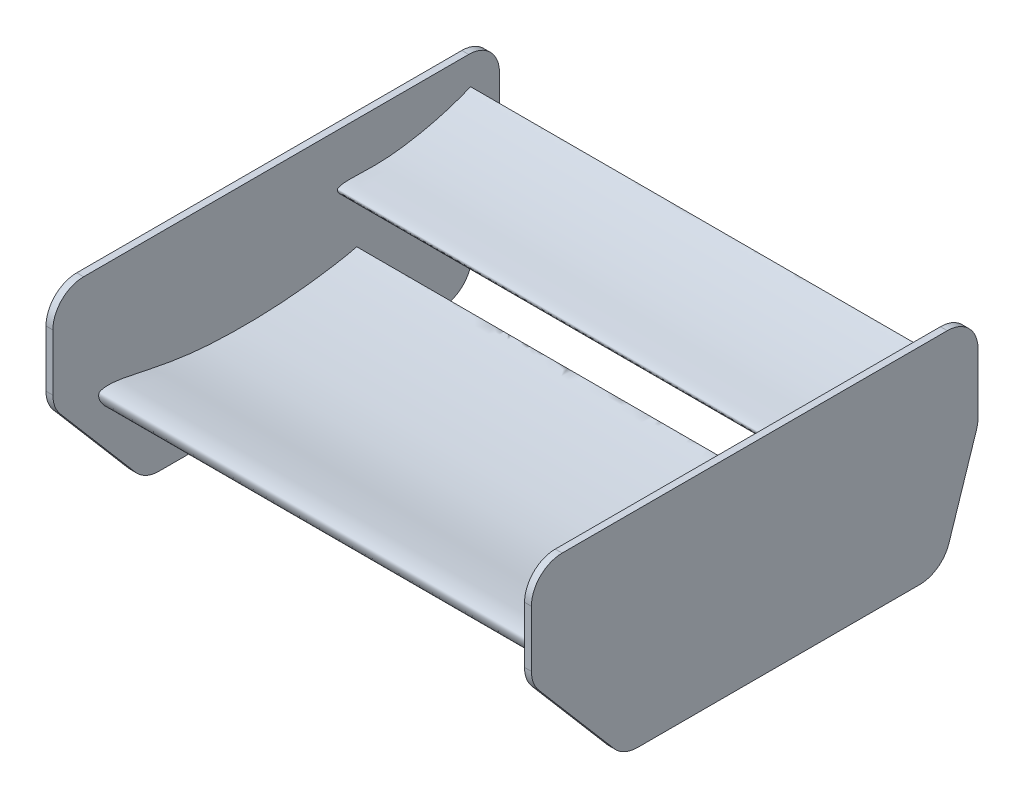
SolidWorks part; units mm, degrees
ref_plane "Front Plane" through (0, 0, 0) normal (0, 0, 1) x (1, 0, 0)
ref_plane "Top Plane" through (0, 0, 0) normal (0, 1, 0) x (1, 0, 0)
ref_plane "Right Plane" through (0, 0, 0) normal (1, 0, 0) x (0, 0, -1)
ref_plane "Soft Top Limit" through (0, 1174.6, 0) normal (0, 1, 0) x (1, 0, 0)
ref_plane "Soft Rear Limit" through (0, 0, -1192.975) normal (0, 0, 1) x (1, 0, 0)
ref_plane "Soft Right Limit" through (-501.65, 0, 0) normal (1, 0, 0) x (0, 0, -1)
ref_plane "Soft Left Limit" through (501.65, 0, 0) normal (1, 0, 0) x (0, 0, -1)
ref_plane "Soft Front Limit" through (0, 0, -165.1) normal (0, 0, 1) x (1, 0, 0)
ref_plane "Slant Limit" through (0, 528.6251, -619.2711) normal (0, -0.6492, 0.7606) x (1, 0, 0)
ref_plane "Bottom" through (0, 476.25, 0) normal (0, 1, 0) x (1, 0, 0)
ref_plane "Midplane" through (0, 0, 0) normal (1, 0, 0) x (0, 0, -1)
curve "Imported Airfoil Curve"
  spline degree 3 poles (0, 2520.0207, 6.126) (0, 2544.889, -1.81) (0, 2521.8965, 7.8839) (0, 2505.3253, 17.7145) (0, 2467.7144, 38.5723) (0, 2424.2142, 62.3813) (0, 2368.0949, 87.8078) (0, 2301.3729, 113.3478) (0, 2223.8362, 140.5377) (0, 2136.6129, 169.2441) (0, 2040.932, 199.097) (0, 1938.2341, 229.6055) (0, 1829.9414, 260.0781) (0, 1717.5266, 289.8586) (0, 1602.4273, 318.1375) (0, 1486.0259, 343.9752) (0, 1369.6902, 366.5754) (0, 1254.3666, 384.7865) (0, 1140.5393, 397.0034) (0, 1028.6357, 403.0127) (0, 919.0585, 402.9406) (0, 812.3986, 397.0375) (0, 709.2785, 385.5985) (0, 610.4299, 369.039) (0, 516.5862, 348.1086) (0, 428.5874, 323.3415) (0, 347.2653, 295.2055) (0, 273.332, 264.2656) (0, 207.4209, 231.0894) (0, 150.0337, 196.3024) (0, 101.596, 160.572) (0, 62.3674, 124.65) (0, 32.4977, 89.3959) (0, 12.0597, 55.6746) (0, 1.683, 26.6201) (0, -0.5567, 6.5526) (0, 0.5894, -3.9947) (0, 1.6947, -9.1451) (0, 2.8711, -12.4915) (0, 3.9449, -14.9776) (0, 4.8993, -16.669) (0, 5.9763, -18.2433) (0, 7.3264, -19.6365) (0, 8.8595, -20.9434) (0, 11.1868, -22.7306) (0, 14.6073, -24.7406) (0, 20.085, -27.4067) (0, 26.8353, -29.9257) (0, 44.6446, -35.1819) (0, 77.8093, -38.8998) (0, 130.2841, -38.2927) (0, 196.3018, -31.4611) (0, 276.2192, -18.4434) (0, 370.8288, 0.8611) (0, 480.7331, 24.811) (0, 605.9792, 50.0099) (0, 745.0759, 74.1542) (0, 895.4497, 95.0846) (0, 1053.6786, 110.004) (0, 1215.6439, 118.3392) (0, 1377.6893, 121.6348) (0, 1537.1174, 120.5125) (0, 1691.5141, 115.2051) (0, 1838.3121, 105.7388) (0, 1975.028, 93.0069) (0, 2099.5942, 78.4581) (0, 2210.5746, 63.1262) (0, 2306.3634, 48.0168) (0, 2387.2069, 33.7158) (0, 2449.0745, 22.0129) (0, 2499.1865, 10.4993) (0, 2520.0207, 6.126) (0, 2544.889, -1.81) (0, 2521.8965, 7.8839) knots -0.016237 -0.007308 -0.001841 0 0.001813 0.006911 0.014576 0.024172 0.035572 0.049013 0.064513 0.081849 0.100772 0.120997 0.142228 0.164173 0.186537 0.209023 0.231367 0.25332 0.274804 0.295858 0.316449 0.336531 0.356033 0.374893 0.39299 0.410197 0.426388 0.441459 0.455334 0.467938 0.479236 0.489204 0.497851 0.505194 0.511308 0.515097 0.516441 0.517273 0.51806 0.518436 0.518797 0.519154 0.519508 0.519887 0.520289 0.52116 0.522116 0.52372 0.525214 0.532575 0.542381 0.554776 0.569931 0.588005 0.609188 0.633329 0.660001 0.688743 0.718873 0.749543 0.780127 0.810209 0.839387 0.867183 0.893104 0.91676 0.937874 0.956199 0.971544 0.983763 0.992692 0.998159 1 1.001813 1.006911 1.014576 periodic
sketch "Airfoils Sketch" plane through (0, 0, 0) normal (1, 0, 0) x (0, 0, -1)
  line L0 (165.1, 1174.6) -> (165.1, 1060.6753) construction
  line L1 (165.1, 1060.6753) -> (663.9798, 476.25) construction
  line L2 (663.9798, 476.25) -> (1192.975, 476.25) construction
  line L3 (1192.975, 476.25) -> (1192.975, 1174.6) construction
  line L4 (1192.975, 1174.6) -> (165.1, 1174.6) construction
  line L5 (509.9361, 1174.6) -> (-509.9361, 1174.6) construction
  line L6 (165.1, 67.0076) -> (165.1, -67.0076) construction
  line L7 (364.7288, 826.8151) -> (873.8134, 230.4351) construction
  line L8 (279.3831, 476.25) -> (-279.3831, 476.25) construction
  line L9 (1192.975, 353.2696) -> (1192.975, -353.2696) construction
  line L10 (364.5896, 498.1423) -> (364.5896, 1393.8577) construction
  line L11 (897.9896, 508.5908) -> (897.9896, 1383.4092) construction
  line L12 (897.9896, 946) -> (364.5896, 946) construction
  line L13 (262.9896, 946) -> (1192.975, 946) construction
  line L14 (848.1751, 1122.607) -> (868.0101, 1010.1175) construction
  line L15 (1123.2328, 1171.6779) -> (1143.263, 1058.0812) construction
  line L16 (1133.2479, 1114.8795) -> (858.0926, 1066.3622) construction
  line L21 (176.2614, 1047.6) -> (1192.975, 1047.6) construction
  spline S0 degree 3 poles (893.7912, 944.7229) (899.0172, 946.3778) (894.1843, 944.3529) (890.6998, 942.2962) (882.7919, 937.9336) (873.6459, 932.9541) (861.8492, 927.6408) (847.826, 922.3086) (831.5308, 916.6349) (813.2009, 910.6474) (793.0943, 904.4229) (771.5139, 898.0641) (748.7586, 891.7155) (725.138, 885.5141) (700.9544, 879.6292) (676.4985, 874.2577) (652.0578, 869.5659) (627.8318, 865.7954) (603.9228, 863.283) (580.4206, 862.0732) (557.4098, 862.1394) (535.0144, 863.4287) (513.3649, 865.8789) (492.6147, 869.4025) (472.9176, 873.8415) (454.4497, 879.0835) (437.3855, 885.0299) (421.8742, 891.5616) (408.0485, 898.5592) (396.0136, 905.8911) (385.8586, 913.417) (377.6374, 920.9787) (371.3813, 928.3959) (367.1052, 935.4868) (364.9396, 941.5929) (364.4786, 945.8081) (364.7242, 948.0225) (364.9587, 949.1035) (365.2073, 949.8057) (365.434, 950.3273) (365.6352, 950.682) (365.8621, 951.0121) (366.1463, 951.304) (366.4688, 951.5778) (366.9584, 951.952) (367.6776, 952.3725) (368.8291, 952.9298) (370.2479, 953.4556) (373.9902, 954.5511) (380.9564, 955.3164) (391.9757, 955.1645) (405.8359, 953.6991) (422.6123, 950.9282) (442.4709, 946.8302) (465.5393, 941.7496) (491.8288, 936.3995) (521.0273, 931.2645) (552.5956, 926.7991) (585.8161, 923.5923) (619.8244, 921.7664) (653.8518, 920.9989) (687.3317, 921.1602) (719.7569, 922.2028) (750.5884, 924.1223) (779.3042, 926.7322) (805.4694, 929.7293) (828.782, 932.8973) (848.9044, 936.0255) (865.8879, 938.991) (878.8853, 941.4197) (889.4141, 943.8142) (893.7912, 944.7229) (899.0172, 946.3778) (894.1843, 944.3529) knots -0.016237 -0.007308 -0.001841 0 0.001813 0.006911 0.014576 0.024172 0.035572 0.049013 0.064513 0.081849 0.100772 0.120997 0.142228 0.164173 0.186537 0.209023 0.231367 0.25332 0.274804 0.295858 0.316449 0.336531 0.356033 0.374893 0.39299 0.410197 0.426388 0.441459 0.455334 0.467938 0.479236 0.489204 0.497851 0.505194 0.511308 0.515097 0.516441 0.517273 0.51806 0.518436 0.518797 0.519154 0.519508 0.519887 0.520289 0.52116 0.522116 0.52372 0.525214 0.532575 0.542381 0.554776 0.569931 0.588005 0.609188 0.633329 0.660001 0.688743 0.718873 0.749543 0.780127 0.810209 0.839387 0.867183 0.893104 0.91676 0.937874 0.956199 0.971544 0.983763 0.992692 0.998159 1 1.001813 1.006911 1.014576 only from (897.9896, 946) to (897.9896, 946)
  spline S1 degree 3 poles (1131.1983, 1113.8389) (1133.7436, 1115.1679) (1131.4347, 1113.6837) (1129.8243, 1112.3058) (1126.1418, 1109.3361) (1121.8768, 1105.9355) (1116.2747, 1102.1216) (1109.5258, 1098.0955) (1101.636, 1093.6865) (1092.7251, 1088.9306) (1082.9193, 1083.8908) (1072.3654, 1078.6477) (1061.2045, 1073.3029) (1049.5838, 1067.9554) (1037.6439, 1062.72) (1025.5169, 1057.7246) (1013.3359, 1053.0813) (1001.1818, 1048.9327) (989.0768, 1045.4619) (977.0633, 1042.7001) (965.1871, 1040.6413) (953.5171, 1039.2693) (942.1263, 1038.564) (931.1018, 1038.4943) (920.5372, 1038.9925) (910.5337, 1040.0168) (901.1902, 1041.5321) (892.5946, 1043.4906) (884.8261, 1045.8428) (877.951, 1048.5303) (872.0279, 1051.4888) (867.0992, 1054.6418) (863.1974, 1057.8989) (860.3465, 1061.1678) (858.674, 1064.1207) (858.0528, 1066.2532) (857.9781, 1067.4178) (858.0007, 1067.9968) (858.0651, 1068.3816) (858.1346, 1068.6713) (858.2061, 1068.8726) (858.2931, 1069.0635) (858.4132, 1069.2399) (858.5547, 1069.4105) (858.7731, 1069.648) (859.1059, 1069.9304) (859.6492, 1070.3226) (860.3333, 1070.7229) (862.1641, 1071.6284) (865.688, 1072.6568) (871.3861, 1073.5807) (878.6693, 1074.0855) (887.5754, 1074.1821) (898.1923, 1073.8745) (910.5543, 1073.3519) (924.6024, 1072.9833) (940.1316, 1072.9902) (956.8223, 1073.5582) (974.2508, 1074.9256) (991.9601, 1077.0771) (1009.5831, 1079.7762) (1026.839, 1082.9048) (1043.4708, 1086.3919) (1059.2007, 1090.1865) (1073.7764, 1094.1448) (1087.0011, 1098.0708) (1098.7388, 1101.8255) (1108.8345, 1105.2695) (1117.3257, 1108.344) (1123.8095, 1110.7791) (1129.023, 1112.972) (1131.1983, 1113.8389) (1133.7436, 1115.1679) (1131.4347, 1113.6837) knots -0.016237 -0.007308 -0.001841 0 0.001813 0.006911 0.014576 0.024172 0.035572 0.049013 0.064513 0.081849 0.100772 0.120997 0.142228 0.164173 0.186537 0.209023 0.231367 0.25332 0.274804 0.295858 0.316449 0.336531 0.356033 0.374893 0.39299 0.410197 0.426388 0.441459 0.455334 0.467938 0.479236 0.489204 0.497851 0.505194 0.511308 0.515097 0.516441 0.517273 0.51806 0.518436 0.518797 0.519154 0.519508 0.519887 0.520289 0.52116 0.522116 0.52372 0.525214 0.532575 0.542381 0.554776 0.569931 0.588005 0.609188 0.633329 0.660001 0.688743 0.718873 0.749543 0.780127 0.810209 0.839387 0.867183 0.893104 0.91676 0.937874 0.956199 0.971544 0.983763 0.992692 0.998159 1 1.001813 1.006911 1.014576 only from (1133.2479, 1114.8795) to (1133.2479, 1114.8795)
  dimension "D1" = 533.4
  dimension "D2" = 228.6
  dimension "D3" = 0
  dimension "D4" = 101.6
  dimension "D5" = 279.4
  dimension "D6" = 59.7205
  dimension "D7" = 10
extrude "Extruded Airfoils" add sketch "Airfoils Sketch" along normal offset from surface (487.45 mm away) 14.2 up to plane "Soft Left Limit"
sketch "Endplate Sketch" plane through (501.65, 0, 0) normal (1, 0, 0) x (0, 0, -1)
  line L6 (333.4477, 1174.6) -> (1129.475, 1174.6)
  line L7 (1192.975, 1174.6) -> (165.1, 1174.6) construction
  line L8 (1192.975, 1111.1) -> (1192.975, 986.6717)
  line L9 (1192.975, 476.25) -> (1192.975, 1174.6) construction
  line L11 (1189.8464, 966.9854) -> (1132.8969, 792.34)
  line L12 (1072.5255, 748.5263) -> (489.1772, 748.5263)
  line L19 (440.8805, 770.7991) -> (285.151, 953.2323)
  line L26 (269.9477, 994.4595) -> (269.9477, 1111.1)
  line L28 (165.1, 1060.6753) -> (663.9798, 476.25) construction
  arc A12 (1129.475, 1174.6) -> (1192.975, 1111.1) centre (1129.475, 1111.1) cw
  arc A13 (1192.975, 986.6717) -> (1189.8464, 966.9854) centre (1129.475, 986.6717) cw
  arc A14 (1132.8969, 792.34) -> (1072.5255, 748.5263) centre (1072.5255, 812.0263) cw
  arc A15 (489.1772, 748.5263) -> (440.8805, 770.7991) centre (489.1772, 812.0263) cw
  arc A16 (285.151, 953.2323) -> (269.9477, 994.4595) centre (333.4477, 994.4595) cw
  arc A17 (333.4477, 1174.6) -> (269.9477, 1111.1) centre (333.4477, 1111.1) ccw
  point P16 (1192.975, 1174.6)
  point P19 (1192.975, 976.5799)
  point P29 (269.9477, 1174.6)
  dimension "D1" = 63.5
extrude "Extruded Endplate" add sketch "Endplate Sketch" against normal up to surface (14.2 mm away)
mirror "Mirror" about plane through (0, 0, 0) normal (1, 0, 0) of bodies 106
ref_point "Point2"
ref_plane "Plane1" through (0, 1143, 0) normal (0, 1, 0) x (1, 0, 0)
sketch "Sketch1" plane through (0, 1143, 0) normal (0, 1, 0) x (1, 0, 0)
  circle A0 centre (0, 139.7) radius 2000 construction
  dimension "D1" = 4000
ref_plane "Plane2" through (0, 0, 0) normal (0, 1, 0) x (1, 0, 0)
sketch "Sketch2" plane through (0, 0, 0) normal (1, 0, 0) x (0, 0, -1)
  line L0 (55, 0) -> (-55, 0) construction
  line L1 (-2459.9326, 1300) -> (2139.7, 1300) construction
  line L2 (-2459.9326, 1300) -> (-2459.9326, 0) construction
  line L3 (-2459.9326, 0) -> (2139.7, 0) construction
  line L4 (2139.7, 1300) -> (2139.7, 0) construction
  line L5 (2139.7, 1300) -> (2139.7, 1143) construction
  dimension "D1" = 1300
